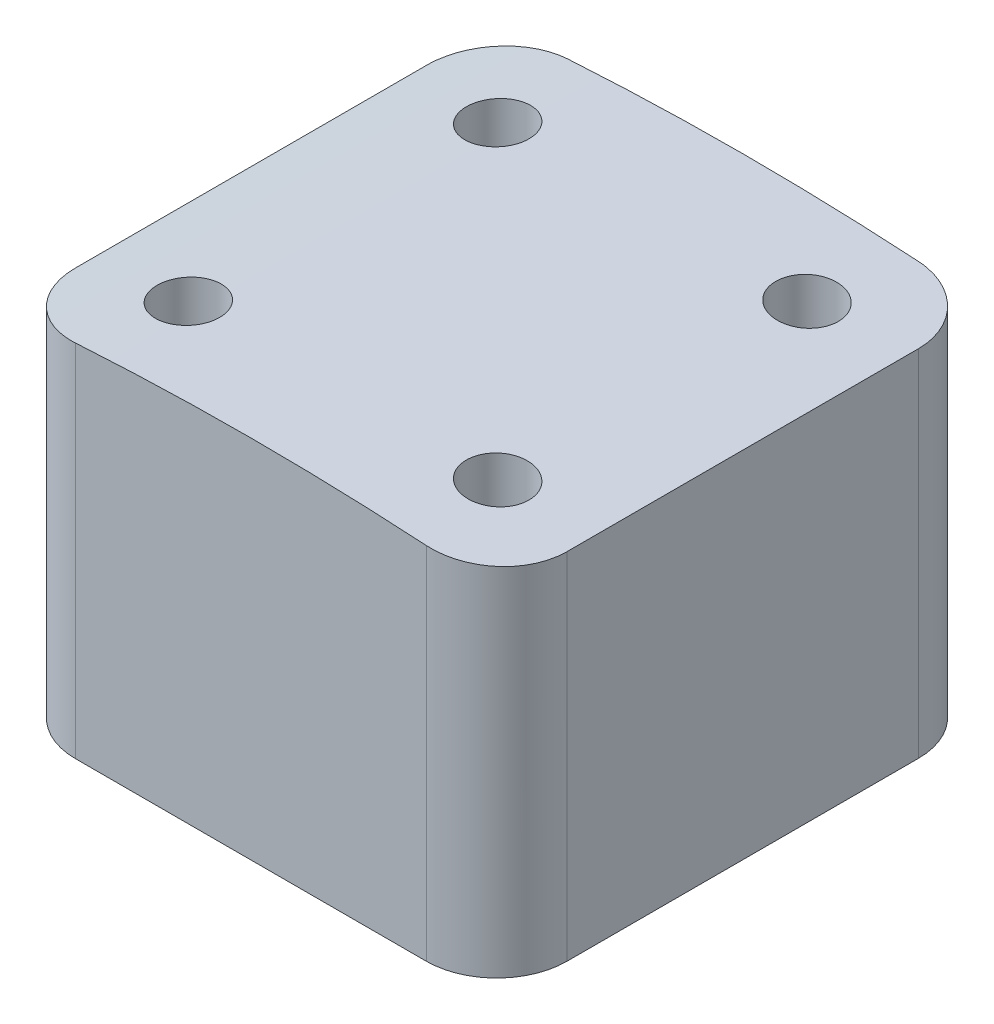
SolidWorks part; units mm, degrees
ref_plane "Front Plane" through (0, 0, 0) normal (0, 0, 1) x (1, 0, 0)
ref_plane "Top Plane" through (0, 0, 0) normal (0, 1, 0) x (1, 0, 0)
ref_plane "Right Plane" through (0, 0, 0) normal (1, 0, 0) x (0, 0, -1)
sketch "Sketch1" plane through (0, 0, 0) normal (0, 0, 1) x (1, 0, 0)
  line L2 (8.8537, 101.3522) -> (8.8537, 88.5344)
  line L3 (8.8537, 88.5344) -> (-8.9026, 88.5344)
  line L4 (-8.9026, 88.5344) -> (-8.9026, 101.3501)
  arc A1 (8.8537, 101.3522) -> (-8.9026, 101.3501) centre (-0.0123, 0.1398) ccw
extrude "Boss-Extrude1" add sketch "Sketch1" along normal blind 8.89 and the other way blind 8.89
sketch "Sketch2" plane through (0, 88.5344, 0) normal (0, -1, 0) x (1, 0, 0)
  circle A0 centre (0, 0) radius 4.7625
hole_wizard "3/8 (0.375) Diameter Slot1" positions "Sketch4" profile "Sketch5" size "3/8" standard "ANSI Inch" slot yes
sketch "Sketch4" plane through (0, 88.5344, 0) normal (0, -1, 0) x (-1, 0, 0)
  point P0 (0, 0)
sketch "Sketch5" plane through (0, 88.5344, 0) normal (1, 0, 0) x (0, 0, -1)
  line L0 (0, 0) -> (0, 12.5136)
  line L1 (0, 12.5136) -> (4.7625, 9.652)
  line L2 (4.7625, 9.652) -> (4.7625, 0)
  line L5 (4.7625, 0) -> (0, 0)
  line L10 (0, 12.5136) -> (-4.7625, 9.652) construction
  line L11 (0, -6.35) -> (0, 107.95) construction
  dimension "Hole Dia." = 9.525
  dimension "Hole Depth" = 9.652
  dimension "Drill Angle" = 118
sketch "Sketch6" plane through (0, 88.5344, 0) normal (0, -1, 0) x (1, 0, 0)
  circle A0 centre (-5.588, -5.588) radius 1.4224
  circle A1 centre (5.588, -5.588) radius 1.4224
  circle A2 centre (5.588, 5.588) radius 1.4224
  circle A3 centre (-5.588, 5.588) radius 1.4224
hole_wizard "Tap Drill for #4-40 Tap1" positions "Sketch8" profile "Sketch9" hole size "#4-40" standard "ANSI Inch" end condition through all
sketch "Sketch8" plane through (0, 88.5344, 0) normal (0, -1, 0) x (-1, 0, 0)
  point P0 (-5.588, 5.588)
  point P3 (5.588, 5.588)
  point P6 (5.588, -5.588)
  point P9 (-5.588, -5.588)
sketch "Sketch9" plane through (5.588, 88.5344, -5.588) normal (1, 0, 0) x (0, 0, -1)
  line L0 (0, 0) -> (0, 13.2054)
  line L1 (0, 13.2054) -> (1.1303, 13.2054)
  line L2 (1.1303, 13.2054) -> (1.1303, 0)
  line L5 (1.1303, 0) -> (0, 0)
  line L11 (0, -6.35) -> (0, 107.95) construction
  dimension "Thru Hole Dia." = 2.2606
  dimension "Thru Hole Depth" = 13.2054
fillet "Fillet1" radius 2.54 4 edges at (-8.9026, 94.9423, 8.89) (-8.9026, 94.9423, -8.89) (8.8537, 94.9433, 8.89) (8.8537, 94.9433, -8.89)
